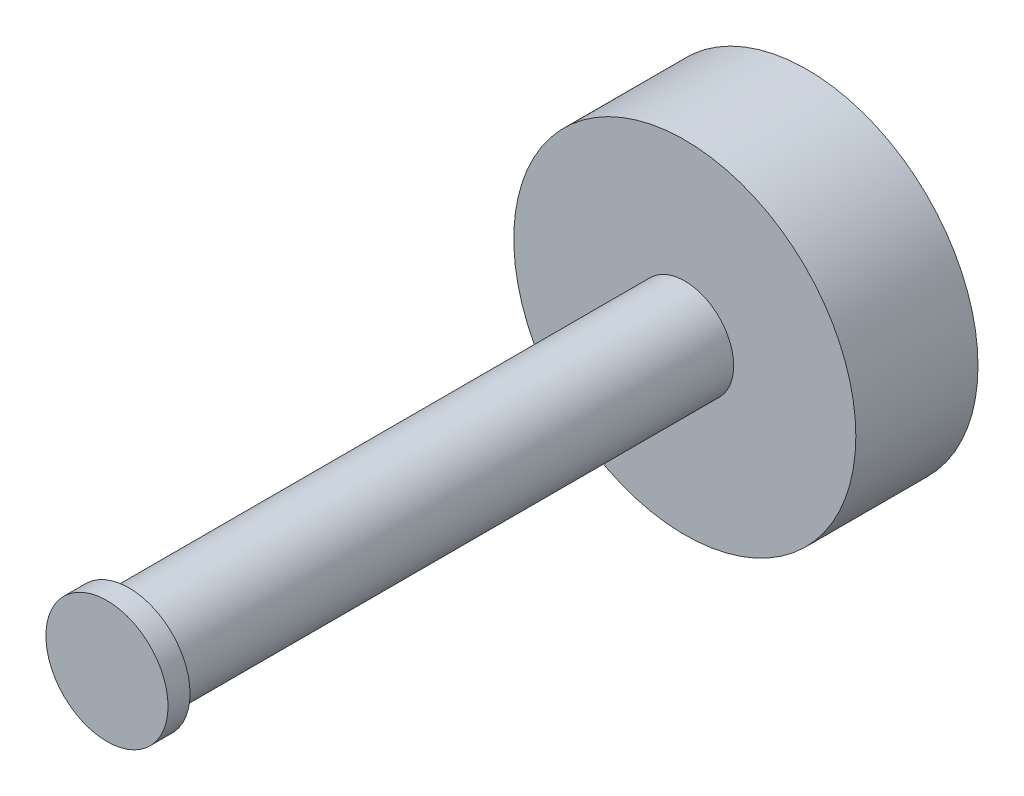
SolidWorks part; units mm, degrees
ref_plane "Front Plane" through (0, 0, 0) normal (0, 0, 1) x (1, 0, 0)
ref_plane "Top Plane" through (0, 0, 0) normal (0, 1, 0) x (1, 0, 0)
ref_plane "Right Plane" through (0, 0, 0) normal (1, 0, 0) x (0, 0, -1)
sketch "Sketch1" plane through (0, 0, 0) normal (0, 0, 1) x (1, 0, 0)
  circle A0 centre (0, 0) radius 14
  circle A1 centre (0, 0) radius 10
  circle A2 centre (0, 0) radius 5.5
extrude "Boss-Extrude1" add sketch "Sketch1" along normal blind 10 contours A0
sketch "Sketch2" plane through (0, 0, 0) normal (0, 0, -1) x (-1, 0, 0)
  circle A0 centre (0, 0) radius 2.25
extrude "Cut-Extrude1" cut sketch "Sketch2" against normal blind 5
sketch "Sketch3" plane through (0, 0, 0) normal (0, 0, -1) x (-1, 0, 0)
  circle A0 centre (0, 0) radius 5
extrude "Cut-Extrude2" cut sketch "Sketch3" against normal blind 1.8
sketch "Sketch11" plane through (0, 0, 10) normal (0, 0, 1) x (1, 0, 0)
  circle A0 centre (0, 0) radius 4
  point P0 (0, 0)
extrude "Boss-Extrude2" add sketch "Sketch11" along normal blind 45.5
sketch "Esboço2" plane through (0, 0, 55.5) normal (0, 0, 1) x (1, 0, 0)
  circle A0 centre (0, 0) radius 5
  dimension "D1" = 10
extrude "Ressalto-extrusão1" add sketch "Esboço2" along normal blind 1.8
